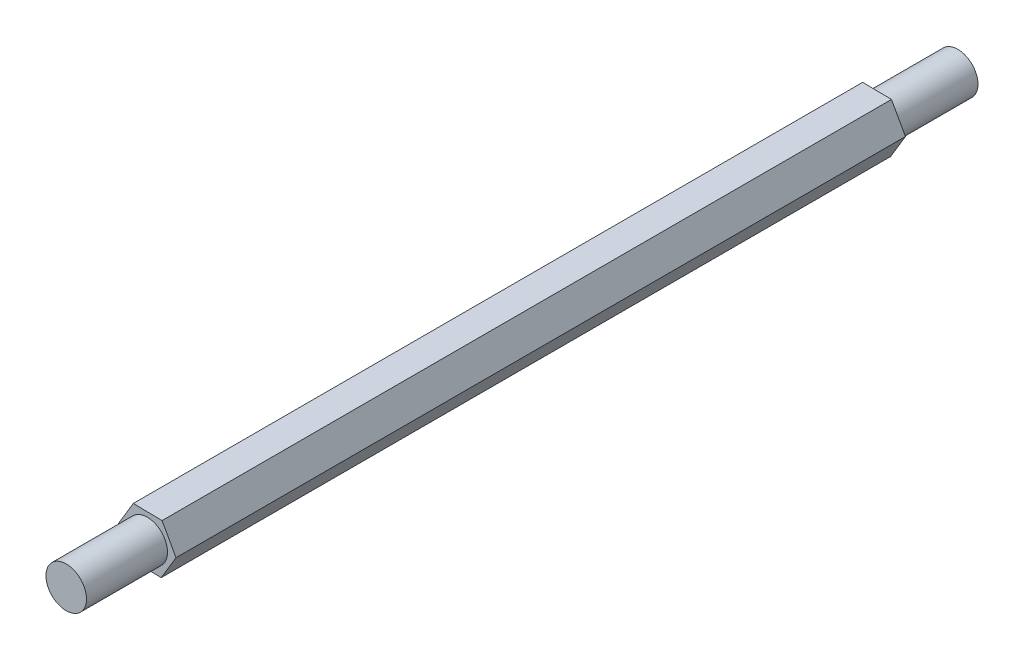
SolidWorks part; units mm, degrees
ref_plane "前视基准面" through (0, 0, 0) normal (0, 0, 1) x (1, 0, 0)
ref_plane "上视基准面" through (0, 0, 0) normal (0, 1, 0) x (1, 0, 0)
ref_plane "右视基准面" through (0, 0, 0) normal (1, 0, 0) x (0, 0, -1)
sketch "草图1" plane through (0, 0, 0) normal (0, 0, 1) x (1, 0, 0)
  circle A0 centre (0, 0) radius 2.5
  dimension "D1" = 5
extrude "凸台-拉伸1" add sketch "草图1" along normal blind 10
sketch "草图2" plane through (0, 0, 10) normal (0, 0, 1) x (1, 0, 0)
  line L1 (3.5492, -0.0569) -> (1.8239, 3.0452)
  line L2 (1.8239, 3.0452) -> (-1.7253, 3.1021)
  line L3 (-1.7253, 3.1021) -> (-3.5492, 0.0569)
  line L4 (-3.5492, 0.0569) -> (-1.8239, -3.0452)
  line L5 (-1.8239, -3.0452) -> (1.7253, -3.1021)
  line L6 (1.7253, -3.1021) -> (3.5492, -0.0569)
  circle A0 centre (0, 0) radius 3.0741 construction
extrude "凸台-拉伸2" add sketch "草图2" along normal blind 90
sketch "草图3" plane through (0, 0, 100) normal (0, 0, 1) x (1, 0, 0)
  circle A0 centre (0, 0) radius 2.5
  dimension "D1" = 5
extrude "凸台-拉伸3" add sketch "草图3" along normal blind 10
